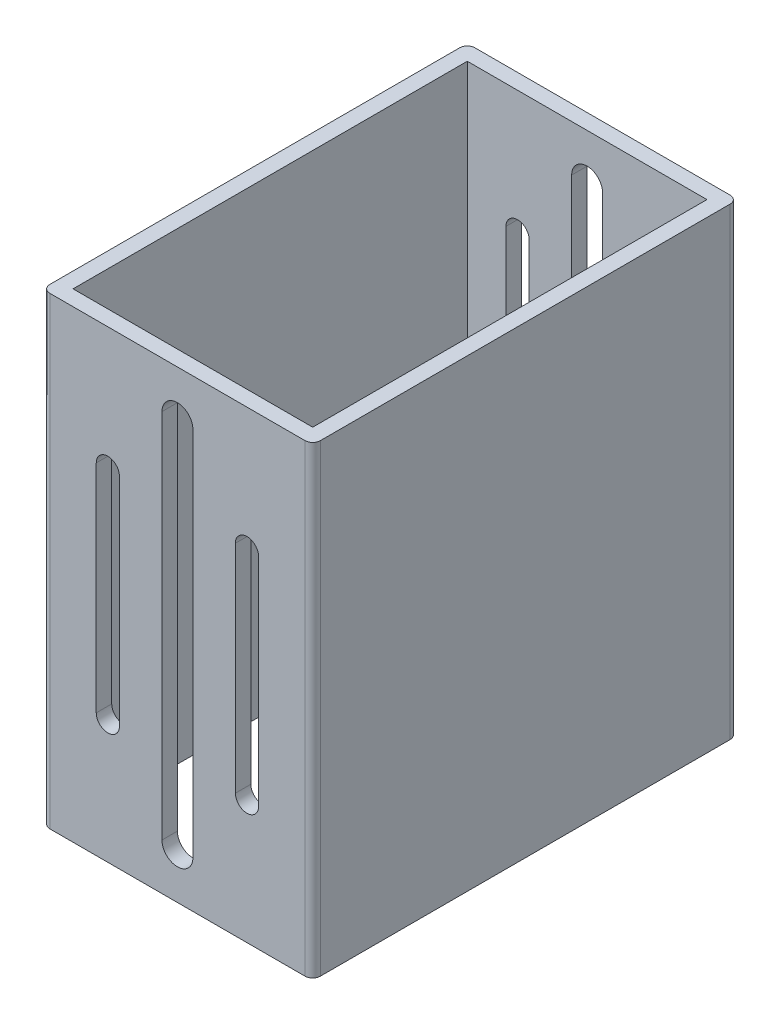
SolidWorks part; units mm, degrees
ref_plane "Front Plane" through (0, 0, 0) normal (0, 0, 1) x (1, 0, 0)
ref_plane "Top Plane" through (0, 0, 0) normal (0, 1, 0) x (1, 0, 0)
ref_plane "Right Plane" through (0, 0, 0) normal (1, 0, 0) x (0, 0, -1)
sketch "Sketch1" plane through (0, 0, 0) normal (0, 1, 0) x (1, 0, 0)
  line L0 (0, 1) -> (0, 54)
  line L1 (1, 55) -> (34, 55)
  line L2 (35, 54) -> (35, 1)
  line L3 (34, 0) -> (1, 0)
  line L4 (2, 53) -> (33, 53)
  line L5 (33, 53) -> (33, 2)
  line L6 (33, 2) -> (2, 2)
  line L7 (2, 2) -> (2, 53)
  arc A0 (0, 1) -> (1, 0) centre (1, 1) ccw
  arc A1 (35, 54) -> (34, 55) centre (34, 54) ccw
  arc A2 (1, 55) -> (0, 54) centre (1, 54) ccw
  arc A3 (35, 1) -> (34, 0) centre (34, 1) cw
  arc A4 (33, 53) -> (33, 53) centre (33, 53) ccw
  arc A5 (33, 2) -> (33, 2) centre (33, 2) cw
  arc A6 (2, 2) -> (2, 2) centre (2, 2) ccw
  arc A7 (2, 53) -> (2, 53) centre (2, 53) ccw
  point P7 (0, 0)
  dimension "D1" = 1
  dimension "D2" = 2
extrude "Boss-Extrude1" add sketch "Sketch1" along normal blind 60
sketch "Sketch3" plane through (0, 0, 0) normal (0, 0, 1) x (1, 0, 0)
  line L0 (17.5, 60) -> (17.5, 0) construction
  line L1 (1, 60) -> (34, 60) construction
  line L2 (1, 0) -> (34, 0) construction
  line L3 (-9.5309, 54) -> (58.7111, 54) construction
  line L4 (-9.5309, 6) -> (56.1409, 6) construction
  line L5 (15.5, 54) -> (15.5, 6)
  line L6 (19.5, 54) -> (19.5, 6)
  line L7 (26.5, 67.325) -> (26.5, -8.1757) construction
  line L8 (-9.5309, 44) -> (58.7111, 44) construction
  line L9 (-14.027, 16) -> (64.9658, 16) construction
  line L10 (28, 44) -> (28, 16)
  line L11 (25, 44) -> (25, 16)
  line L12 (8.5, 67.325) -> (8.5, -8.1757) construction
  line L13 (7, 44) -> (7, 16)
  line L14 (10, 44) -> (10, 16)
  arc A0 (19.5, 54) -> (15.5, 54) centre (17.5, 54) ccw
  arc A1 (15.5, 6) -> (19.5, 6) centre (17.5, 6) ccw
  arc A2 (28, 44) -> (25, 44) centre (26.5, 44) ccw
  arc A3 (25, 16) -> (28, 16) centre (26.5, 16) ccw
  arc A4 (10, 16) -> (7, 16) centre (8.5, 16) cw
  arc A5 (7, 44) -> (10, 44) centre (8.5, 44) cw
  dimension "D3" = 9
  dimension "D1" = 6
  dimension "D2" = 6
  dimension "D4" = 10
  dimension "D5" = 10
extrude "Cut-Extrude1" cut sketch "Sketch3" against normal blind 60
